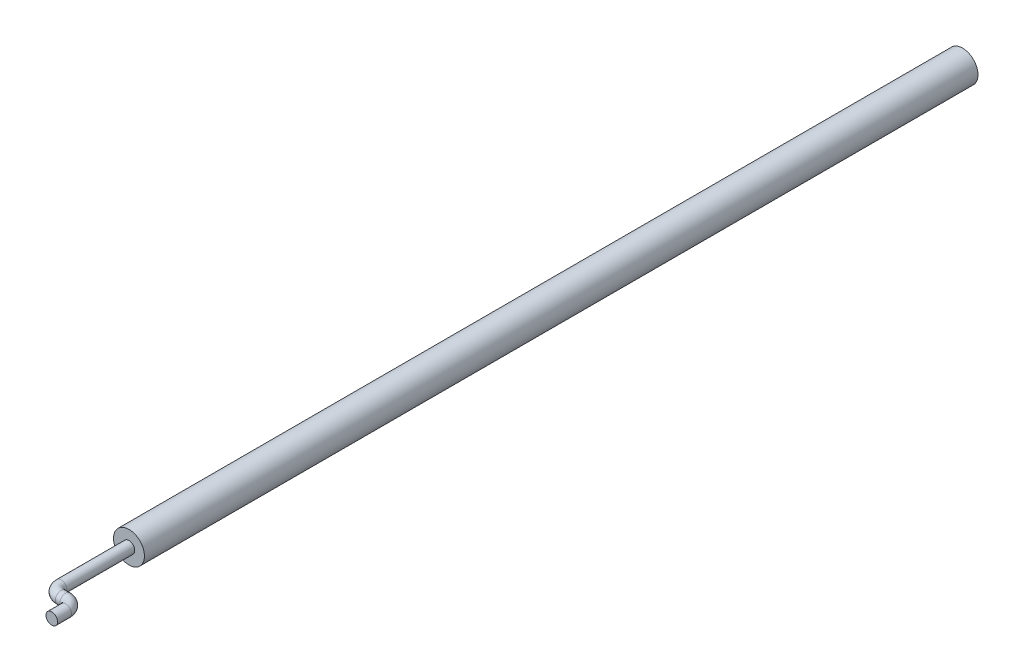
SolidWorks part; units mm, degrees
ref_plane "Front Plane" through (0, 0, 0) normal (0, 0, 1) x (1, 0, 0)
ref_plane "Top Plane" through (0, 0, 0) normal (0, 1, 0) x (1, 0, 0)
ref_plane "Right Plane" through (0, 0, 0) normal (1, 0, 0) x (0, 0, -1)
sketch "Sketch1" plane through (0, 0, 0) normal (0, 0, 1) x (1, 0, 0)
  circle A0 centre (0, 0) radius 50.8
  dimension "D1" = 101.6
extrude "Boss-Extrude1" add sketch "Sketch1" along normal blind 2743.2
sketch3d "3DSketch1"
  line L0 (0, 0, 2743.2) -> (0, 0, 2966.72)
  line L1 (0, 0, 2743.2) -> (0, 0, 0) construction
  line L2 (30.48, 0, 2997.2) -> (45.72, 0, 2997.2)
  line L3 (76.2, 0, 3027.68) -> (76.2, 0, 3073.4)
  arc A0 (45.72, 0, 2997.2) -> (76.2, 0, 3027.68) centre (45.72, 0, 3027.68) ccw
  arc A1 (30.48, 0, 2997.2) -> (0, 0, 2966.72) centre (30.48, 0, 2966.72) ccw
  point P8 (76.2, 0, 2997.2)
  point P9 (45.72, -30.48, 3027.68)
  point P12 (0, 0, 2997.2)
  point P13 (30.48, -30.48, 2966.72)
  dimension "D4" = 30.48
  dimension "D1" = 254
  dimension "D2" = 76.2
  dimension "D3" = 76.2
sketch "Sketch6" plane through (0, 0, 2743.2) normal (0, 0, 1) x (1, 0, 0)
  circle A0 centre (0, 0) radius 19.05
  dimension "D1" = 38.1
sweep "Sweep1" add profiles "Sketch6" path "3DSketch1"
